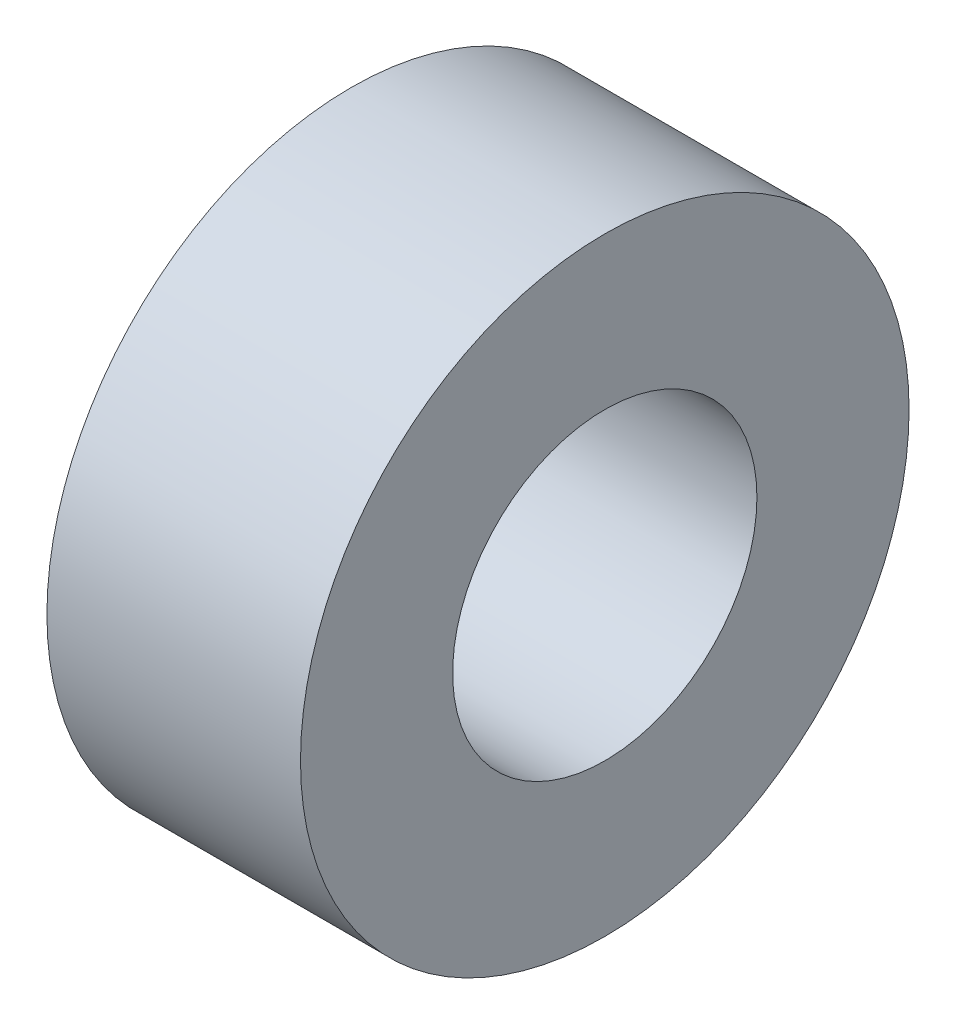
SolidWorks part; units mm, degrees
ref_plane "Front Plane" through (0, 0, 0) normal (0, 0, 1) x (1, 0, 0)
ref_plane "Top Plane" through (0, 0, 0) normal (0, 1, 0) x (1, 0, 0)
ref_plane "Right Plane" through (0, 0, 0) normal (1, 0, 0) x (0, 0, -1)
sketch "Sketch1" plane through (0, 0, 0) normal (1, 0, 0) x (0, 0, -1)
  circle A0 centre (0, 0) radius 1.5
  circle A1 centre (0, 0) radius 3
  dimension "D1" = 6
  dimension "D2" = 3
extrude "Boss-Extrude1" add sketch "Sketch1" along normal mid plane 2.5
